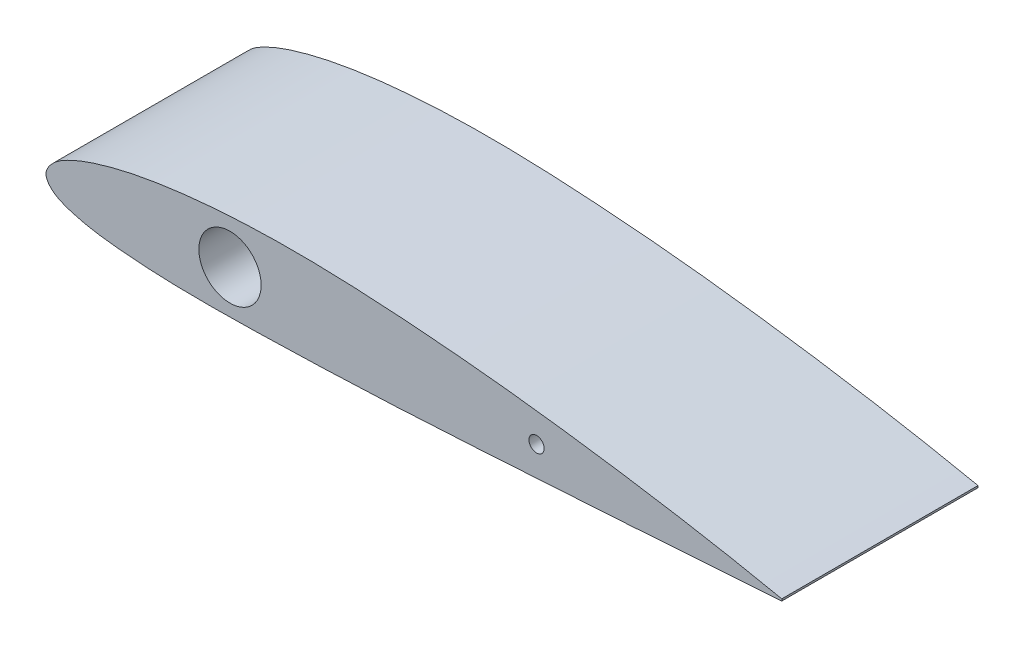
SolidWorks part; units mm, degrees
ref_plane "Front Plane" through (0, 0, 0) normal (0, 0, 1) x (1, 0, 0)
ref_plane "Top Plane" through (0, 0, 0) normal (0, 1, 0) x (1, 0, 0)
ref_plane "Right Plane" through (0, 0, 0) normal (1, 0, 0) x (0, 0, -1)
curve "Curve1"
  spline degree 3 poles (1, 0.0013, 0) (0.9833, 0.0047, 0) (0.9501, 0.0115, 0) (0.8835, 0.024, 0) (0.8002, 0.0379, 0) (0.7002, 0.0522, 0) (0.6002, 0.0641, 0) (0.5001, 0.0729, 0) (0.4001, 0.0788, 0) (0.3166, 0.0798, 0) (0.2499, 0.077, 0) (0.1999, 0.073, 0) (0.1498, 0.0666, 0) (0.108, 0.0587, 0) (0.0748, 0.0498, 0) (0.0496, 0.0416, 0) (0.0282, 0.0322, 0) (0.0098, 0.0207, 0) (-0.0063, 0.0009, 0) (0.0104, -0.0165, 0) (0.0285, -0.0245, 0) (0.0497, -0.0305, 0) (0.0749, -0.0348, 0) (0.1083, -0.0385, 0) (0.1499, -0.0414, 0) (0.2, -0.0425, 0) (0.25, -0.0424, 0) (0.3167, -0.0409, 0) (0.4, -0.0382, 0) (0.5, -0.0336, 0) (0.6, -0.0276, 0) (0.7, -0.0214, 0) (0.8, -0.0151, 0) (0.8833, -0.0093, 0) (0.95, -0.0048, 0) (0.9833, -0.0025, 0) (1, -0.0013, 0) knots 0 0 0 0 0.025012 0.049959 0.099673 0.149206 0.198581 0.247805 0.296917 0.345953 0.370492 0.395091 0.419815 0.444799 0.45749 0.470406 0.483879 0.491264 0.503459 0.513609 0.520451 0.533235 0.545691 0.558032 0.582609 0.607135 0.631652 0.656174 0.705234 0.75432 0.803437 0.852566 0.901701 0.950849 0.975423 1 1 1 1
sketch "Sketch1" plane through (0, 0, 0) normal (0, 0, 1) x (1, 0, 0)
  line L0 (-30.2439, 0) -> (269.7561, 0) construction
  line L1 (269.7561, 0.39) -> (269.7561, -0.39)
  circle A0 centre (44.7561, 5) radius 12.7
  circle A1 centre (169.7561, 5) radius 3.1
  spline S1 degree 3 poles (269.7561, 0.39) (264.7588, 1.414) (254.7775, 3.4593) (234.7977, 7.2056) (209.8095, 11.3564) (179.8038, 15.6525) (149.8031, 19.2352) (119.7893, 21.8586) (89.7824, 23.6351) (64.7467, 23.9358) (44.7379, 23.1075) (29.719, 21.8937) (14.6812, 19.9716) (2.166, 17.6048) (-7.8114, 14.927) (-15.3757, 12.4925) (-21.7845, 9.6559) (-27.3126, 6.2169) (-32.1334, 0.2696) (-27.1259, -4.9579) (-21.7011, -7.3422) (-15.3205, -9.1532) (-7.7812, -10.4518) (2.2361, -11.56) (14.7402, -12.4129) (29.7543, -12.7549) (44.7577, -12.7072) (64.7596, -12.2657) (89.7642, -11.4712) (119.7661, -10.0886) (149.7593, -8.2916) (179.7575, -6.4237) (209.7609, -4.5329) (234.7555, -2.7916) (254.7573, -1.4485) (264.7563, -0.7428) (269.7561, -0.39) knots 0 0 0 0 0.025012 0.049959 0.099673 0.149206 0.198581 0.247805 0.296917 0.345953 0.370492 0.395091 0.419815 0.444799 0.45749 0.470406 0.483879 0.491264 0.503459 0.513609 0.520451 0.533235 0.545691 0.558032 0.582609 0.607135 0.631652 0.656174 0.705234 0.75432 0.803437 0.852566 0.901701 0.950849 0.975423 1 1 1 1
  point P3 (44.7561, 5)
  point P11 (194.7561, 0)
  dimension "D3" = 75
  dimension "D4" = 25.4
  dimension "D1" = 6.2
  dimension "D2" = 5
  dimension "D5" = 75
  dimension "D6" = 25
extrude "Boss-Extrude1" add sketch "Sketch1" along normal blind 80
move or copy body "Body-Move/Copy1" bodies to move or copy 101 copy no translate (270, 0, 270) parameters "D1"=270, "D2"=0, "D3"=270
